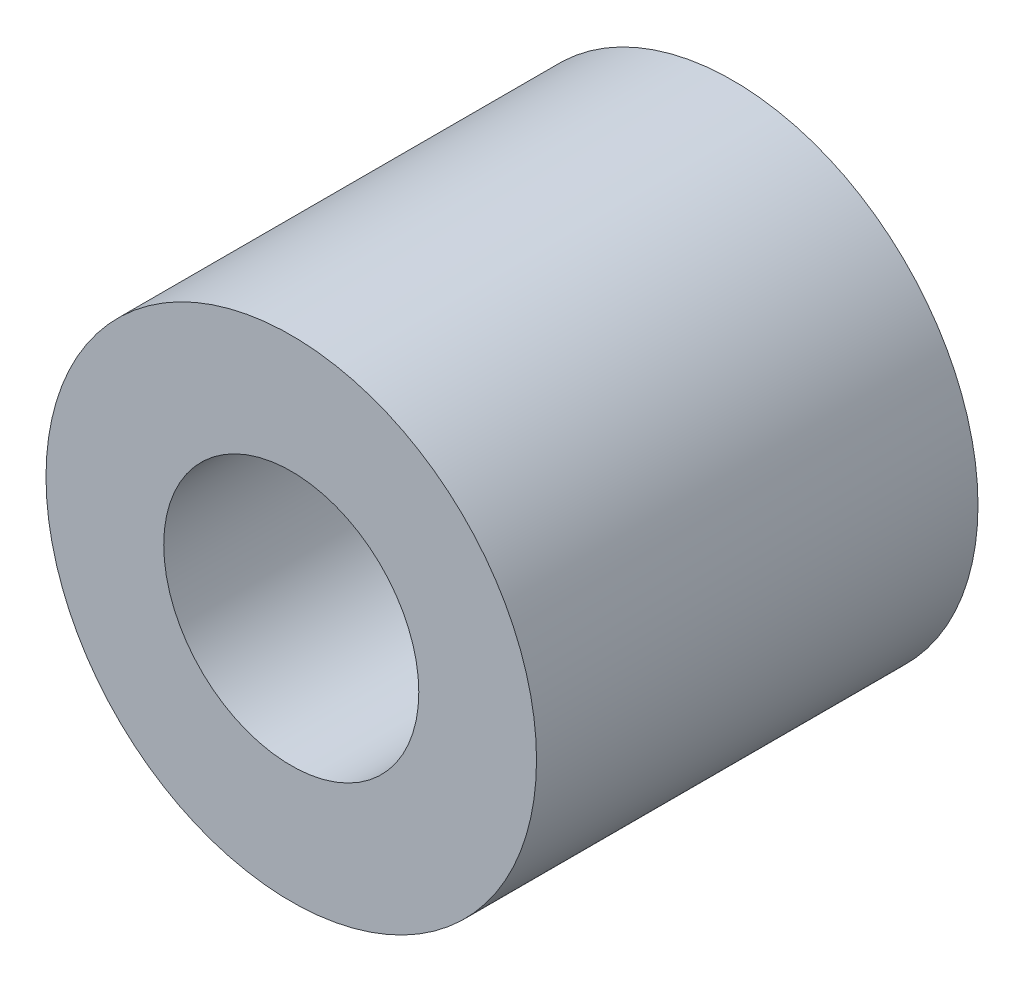
SolidWorks part; units mm, degrees
ref_plane "Front Plane" through (0, 0, 0) normal (0, 0, 1) x (1, 0, 0)
ref_plane "Top Plane" through (0, 0, 0) normal (0, 1, 0) x (1, 0, 0)
ref_plane "Right Plane" through (0, 0, 0) normal (1, 0, 0) x (0, 0, -1)
sketch "Sketch1" plane through (0, 0, 0) normal (0, 0, 1) x (1, 0, 0)
  circle A0 centre (0, 0) radius 6.35
  circle A1 centre (0, 0) radius 3.302
  dimension "D1" = 12.7
  dimension "D2" = 6.604
extrude "Boss-Extrude1" add sketch "Sketch1" along normal blind 11.43
